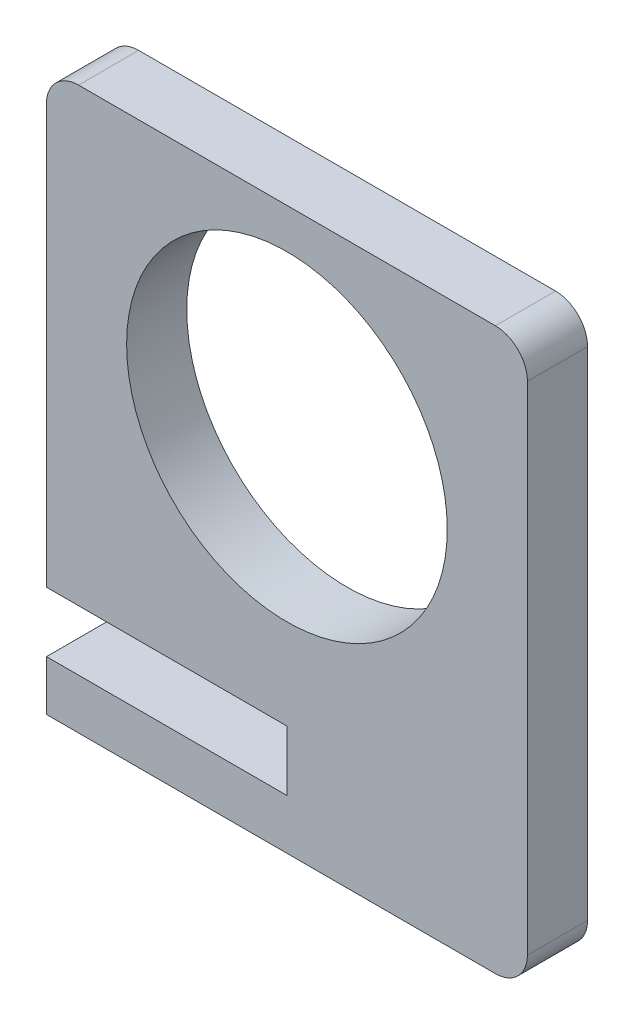
SolidWorks part; units mm, degrees
material "Corrugated Paper"
ref_plane "Front Plane" through (0, 0, 0) normal (0, 0, 1) x (1, 0, 0)
ref_plane "Top Plane" through (0, 0, 0) normal (0, 1, 0) x (1, 0, 0)
ref_plane "Right Plane" through (0, 0, 0) normal (1, 0, 0) x (0, 0, -1)
sketch "Sketch1" plane through (0, 0, 0) normal (0, 0, 1) x (1, 0, 0)
  line L0 (-19.05, 2.3813) -> (-19.05, 6.35)
  line L1 (-19.05, -2.3813) -> (0, -2.3813)
  line L3 (-19.05, 2.3813) -> (0, 2.3813)
  line L4 (0, -2.3813) -> (0, 2.3813)
  line L5 (-19.05, 6.35) -> (19.05, 6.35)
  line L6 (0, 0) -> (19.05, 0) construction
  line L7 (19.05, 6.35) -> (19.05, -6.35)
  line L8 (-19.05, -6.35) -> (19.05, -6.35)
  line L9 (-19.05, -2.3813) -> (-19.05, -6.35)
  line L10 (-19.05, 38.1) -> (19.05, 6.35) construction
  line L11 (-19.05, 6.35) -> (19.05, 6.35)
  line L12 (-19.05, 6.35) -> (-19.05, 38.1)
  line L13 (-19.05, 38.1) -> (19.05, 38.1)
  line L14 (19.05, 6.35) -> (19.05, 38.1)
  line L15 (19.05, 38.1) -> (-19.05, 6.35) construction
  circle A0 centre (0, 22.225) radius 12.7
  dimension "D6" = 25.4
  dimension "D1" = 19.05
  dimension "D2" = 4.7625
  dimension "D3" = 19.05
  dimension "D4" = 12.7
  dimension "D5" = 44.45
extrude "Boss-Extrude1" add sketch "Sketch1" along normal mid plane 4.7625 contours L5 L14 L13 L12 | L6 L4 L1 L9 L8 L7 | L4 L6 L7 L5 L0 L3
fillet "Fillet1" radius 2.54 3 edges at (19.05, -6.35, 0) (-19.05, 38.1, 0) (19.05, 38.1, 0)
equation "\"D2@Sketch1\" = \"thick\""
equation "\"D1@Boss-Extrude1\"= \"thick\""
equation "\"rodThick\"= 3/16in"
equation "\"thick\"= 3/16in"
